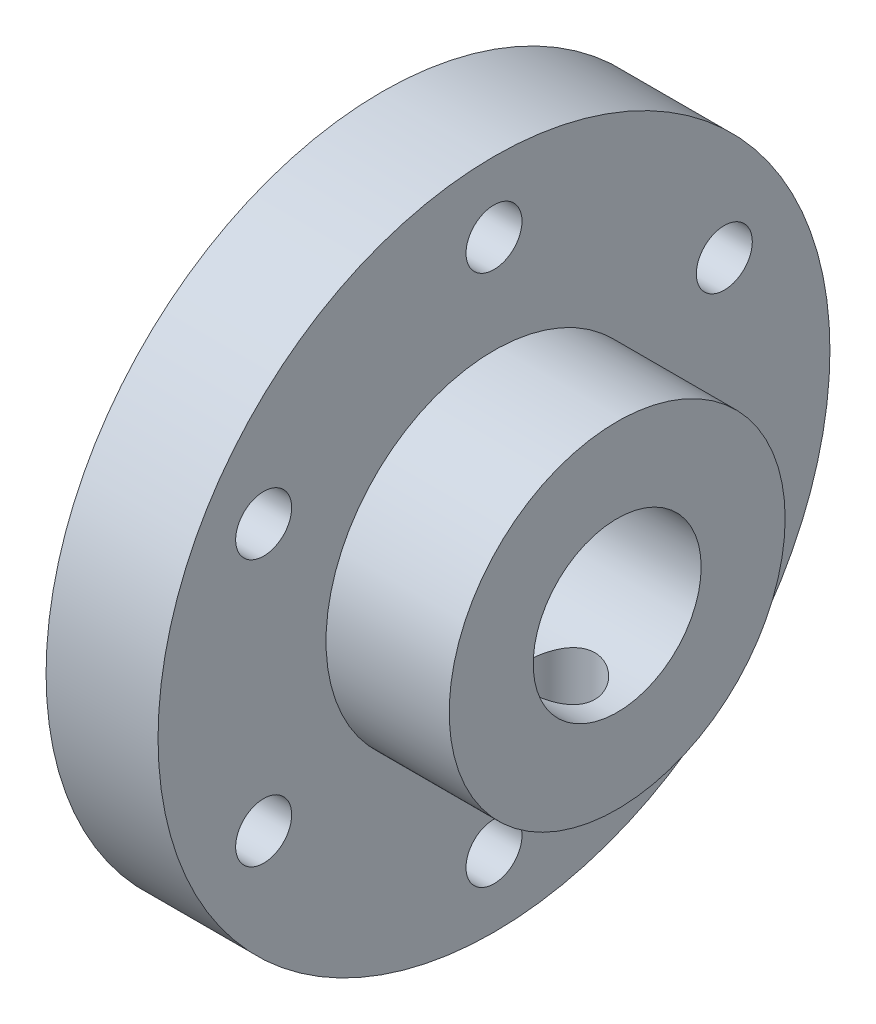
SolidWorks part; units mm, degrees
material "201 Annealed Stainless Steel (SS)"
ref_plane "Front Plane" through (0, 0, 0) normal (0, 0, 1) x (1, 0, 0)
ref_plane "Top Plane" through (0, 0, 0) normal (0, 1, 0) x (1, 0, 0)
ref_plane "Right Plane" through (0, 0, 0) normal (1, 0, 0) x (0, 0, -1)
sketch "Sketch1" plane through (0, 0, 0) normal (1, 0, 0) x (0, 0, -1)
  circle A0 centre (0, 0) radius 30
  dimension "D1" = 60
extrude "Boss-Extrude1" add sketch "Sketch1" along normal blind 10
sketch "Sketch2" plane through (10, 0, 0) normal (1, 0, 0) x (0, 0, -1)
  circle A0 centre (0, 23.75) radius 2.5
  circle A1 centre (20.5681, 11.875) radius 2.5
  circle A2 centre (20.5681, -11.875) radius 2.5
  circle A3 centre (0, -23.75) radius 2.5
  circle A4 centre (-20.5681, -11.875) radius 2.5
  circle A5 centre (-20.5681, 11.875) radius 2.5
  point P16 (0, 0)
  dimension "D1" = 23.75
  dimension "D3" = 5
  dimension "D2" = 6
extrude "Cut-Extrude1" cut sketch "Sketch2" against normal through all
sketch "Sketch5" plane through (0, 0, 0) normal (-1, 0, 0) x (0, 0, 1)
  circle A1 centre (0, 0) radius 14
  dimension "D1" = 28
extrude "Boss-Extrude4" add sketch "Sketch5" along normal blind 6
sketch "Sketch8" plane through (10, 0, 0) normal (1, 0, 0) x (0, 0, -1)
  circle A0 centre (0, 0) radius 15
  dimension "D2" = 30
extrude "Boss-Extrude6" add sketch "Sketch8" along normal blind 1
ref_plane "Plane3" through (0, -15, 0) normal (0, -1, 0) x (-1, 0, 0)
sketch "Sketch13" plane through (11, 0, 0) normal (1, 0, 0) x (0, 0, -1)
  circle A0 centre (0, 0) radius 15
  dimension "D1" = 30
extrude "Boss-Extrude7" add sketch "Sketch13" along normal blind 10
sketch "Sketch14" plane through (21, 0, 0) normal (1, 0, 0) x (0, 0, -1)
  line L1 (0, 0) -> (2.2801, 0) construction
  line L10 (3.873, 1) -> (4.873, 1)
  line L11 (4.873, -1) -> (4.873, 1)
  line L12 (3.873, -1) -> (4.873, -1)
  arc A3 (3.873, 1) -> (3.873, -1) centre (0, 0) ccw
  circle A4 centre (0, 0) radius 7.5
  point P22 (0, 0)
  dimension "D1" = 8
  dimension "D2" = 1
  dimension "D3" = 2
extrude "Cut-Extrude4" cut sketch "Sketch14" against normal up to next contours A4
sketch "Sketch12" plane through (0, -15, 0) normal (0, -1, 0) x (-1, 0, 0)
  line L0 (-21, 15) -> (-21, -15) construction
  circle A0 centre (-16, 0) radius 3
  dimension "D1" = 6
  dimension "D2" = 5
extrude "Cut-Extrude3" cut sketch "Sketch12" against normal up to next
